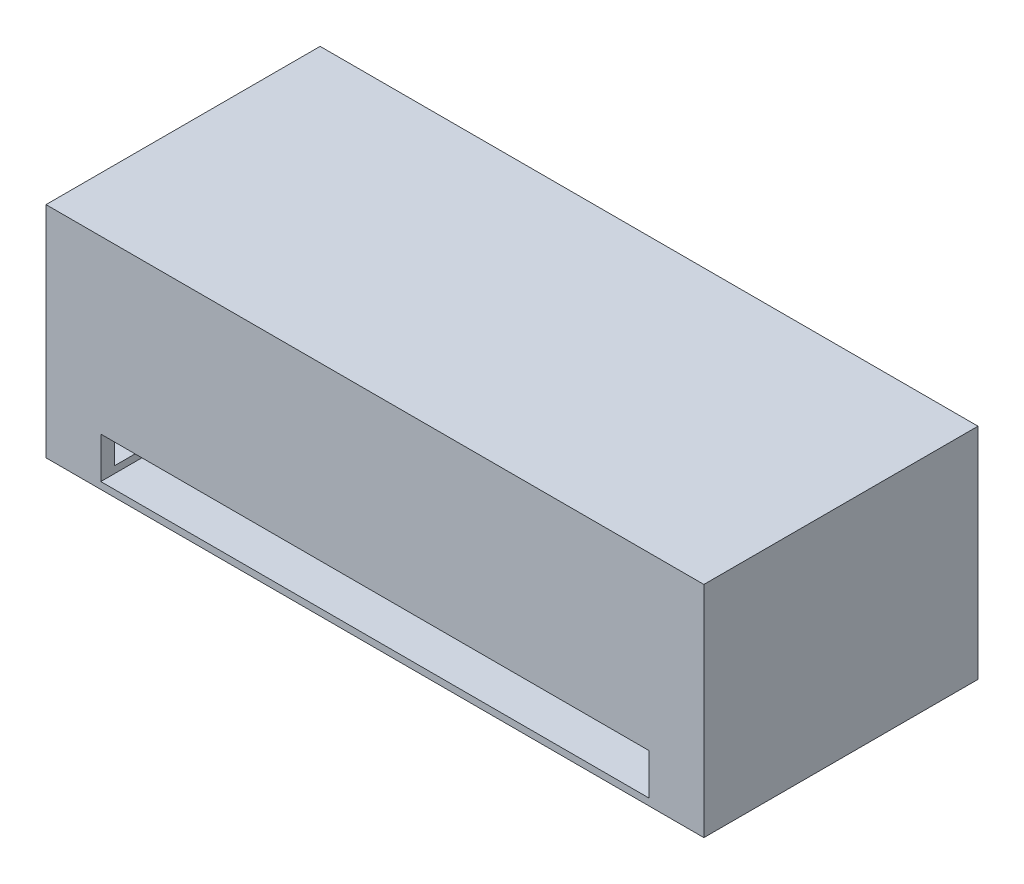
SolidWorks part; units mm, degrees
ref_plane "Front Plane" through (0, 0, 0) normal (0, 0, 1) x (1, 0, 0)
ref_plane "Top Plane" through (0, 0, 0) normal (0, 1, 0) x (1, 0, 0)
ref_plane "Right Plane" through (0, 0, 0) normal (1, 0, 0) x (0, 0, -1)
sketch "Sketch1" plane through (0, 0, 0) normal (0, 1, 0) x (1, 0, 0)
  line L1 (-152.4, -63.5) -> (152.4, -63.5)
  line L2 (-152.4, -63.5) -> (-152.4, 63.5)
  line L3 (-152.4, 63.5) -> (152.4, 63.5)
  line L4 (152.4, -63.5) -> (152.4, 63.5)
  line L5 (-152.4, -63.5) -> (152.4, 63.5) construction
  line L6 (-152.4, 63.5) -> (152.4, -63.5) construction
  point P0 (0, 0)
  dimension "D1" = 304.8
  dimension "D2" = 127
extrude "Boss-Extrude1" add sketch "Sketch1" along normal blind 101.6
shell "Shell1" thickness 6.35
sketch "Sketch2" plane through (0, 0, 63.5) normal (0, 0, 1) x (1, 0, 0)
  line L1 (-127, 3.175) -> (127, 3.175)
  line L2 (-127, 3.175) -> (-127, 22.225)
  line L3 (-127, 22.225) -> (127, 22.225)
  line L4 (127, 3.175) -> (127, 22.225)
  line L5 (-127, 3.175) -> (127, 22.225) construction
  line L6 (-127, 22.225) -> (127, 3.175) construction
  point P0 (0, 12.7)
  point P5 (0, 0)
  dimension "D1" = 254
  dimension "D2" = 19.05
  dimension "D3" = 12.7
extrude "Cut-Extrude1" cut sketch "Sketch2" against normal through all both and the other way through all
